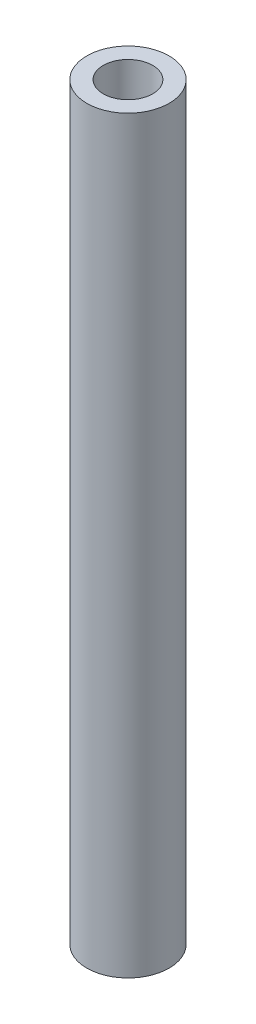
SolidWorks part; units mm, degrees
material "碳板"
ref_plane "前视基准面" through (0, 0, 0) normal (0, 0, 1) x (1, 0, 0)
ref_plane "上视基准面" through (0, 0, 0) normal (0, 1, 0) x (1, 0, 0)
ref_plane "右视基准面" through (0, 0, 0) normal (1, 0, 0) x (0, 0, -1)
sketch "草图1" plane through (0, 0, 0) normal (0, 1, 0) x (1, 0, 0)
  circle A0 centre (0, 0) radius 2.5
  circle A1 centre (0, 0) radius 1.5
  dimension "D1" = 5
  dimension "D2" = 1
extrude "凸台-拉伸1" add sketch "草图1" along normal blind 45.5
